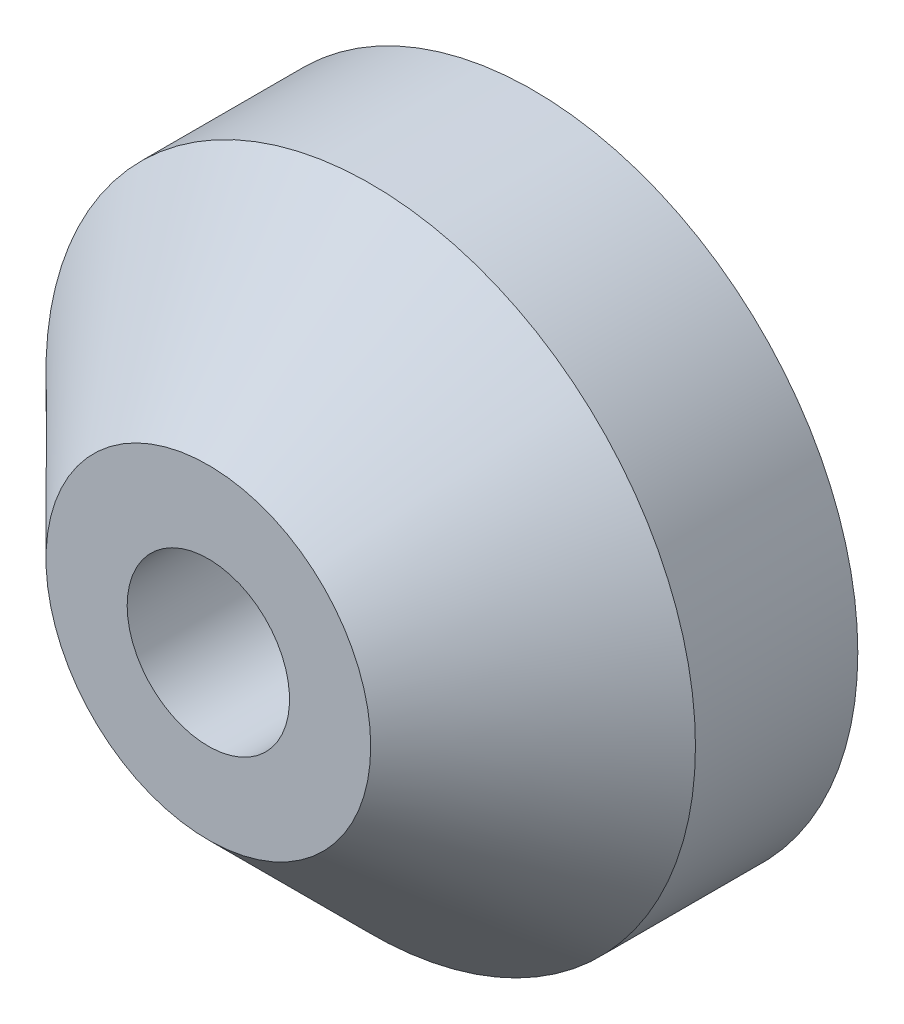
SolidWorks part; units mm, degrees
ref_plane "前视基准面" through (0, 0, 0) normal (0, 0, 1) x (1, 0, 0)
ref_plane "上视基准面" through (0, 0, 0) normal (0, 1, 0) x (1, 0, 0)
ref_plane "右视基准面" through (0, 0, 0) normal (1, 0, 0) x (0, 0, -1)
other "Configuration Table"
sketch "Sketch1" plane through (0, 0, 0) normal (0, 0, 1) x (1, 0, 0)
  circle A0 centre (0, 0) radius 5
  dimension "D1" = 10
extrude "Boss-Extrude1" add sketch "Sketch1" along normal blind 5
chamfer "Chamfer1" distance 2.5 angle 45 1 edges at (5, 0, 5)
sketch "Sketch2" plane through (0, 0, 0) normal (0, 0, -1) x (-1, 0, 0)
  circle A0 centre (0, 0) radius 1.25
  dimension "D1" = 2.5
extrude "Cut-Extrude1" cut sketch "Sketch2" against normal blind 5
sketch "Sketch3" plane through (0, 0, 0) normal (0, 0, -1) x (-1, 0, 0)
  circle A0 centre (0, 0) radius 2.5
  dimension "D1" = 5
extrude "Cut-Extrude2" cut sketch "Sketch3" against normal blind 2.5
